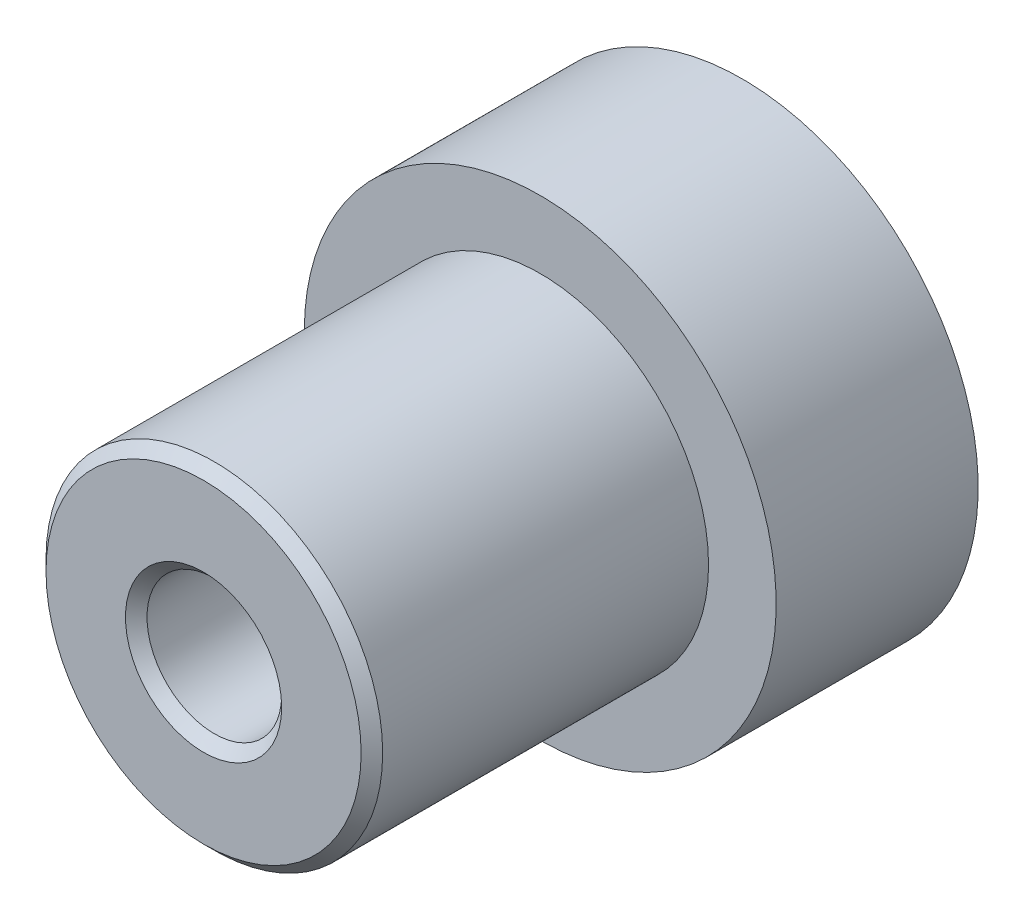
SolidWorks part; units mm, degrees
material "Nylon 6/10"
ref_plane "Front Plane" through (0, 0, 0) normal (0, 0, 1) x (1, 0, 0)
ref_plane "Top Plane" through (0, 0, 0) normal (0, 1, 0) x (1, 0, 0)
ref_plane "Right Plane" through (0, 0, 0) normal (1, 0, 0) x (0, 0, -1)
sketch "Sketch1" plane through (0, 0, 0) normal (0, 0, 1) x (1, 0, 0)
  circle A0 centre (0, 0) radius 5.5626
  dimension "D1" = 11.1252
extrude "Boss-Extrude1" add sketch "Sketch1" along normal blind 4.7625
sketch "Sketch2" plane through (0, 0, 4.7625) normal (0, 0, 1) x (1, 0, 0)
  circle A0 centre (0, 0) radius 3.9688
  dimension "D1" = 7.9375
extrude "Boss-Extrude2" add sketch "Sketch2" along normal blind 7.9375
sketch "Sketch3" plane through (0, 0, 0) normal (0, 0, -1) x (-1, 0, 0)
  circle A0 centre (0, 0) radius 1.5875
  dimension "D1" = 3.175
extrude "Cut-Extrude1" cut sketch "Sketch3" against normal through all
chamfer "Chamfer1" distance 0.254 angle 45 3 edges at (-1.5875, 0, 0) (-1.5875, 0, 12.7) (3.9688, 0, 12.7)
